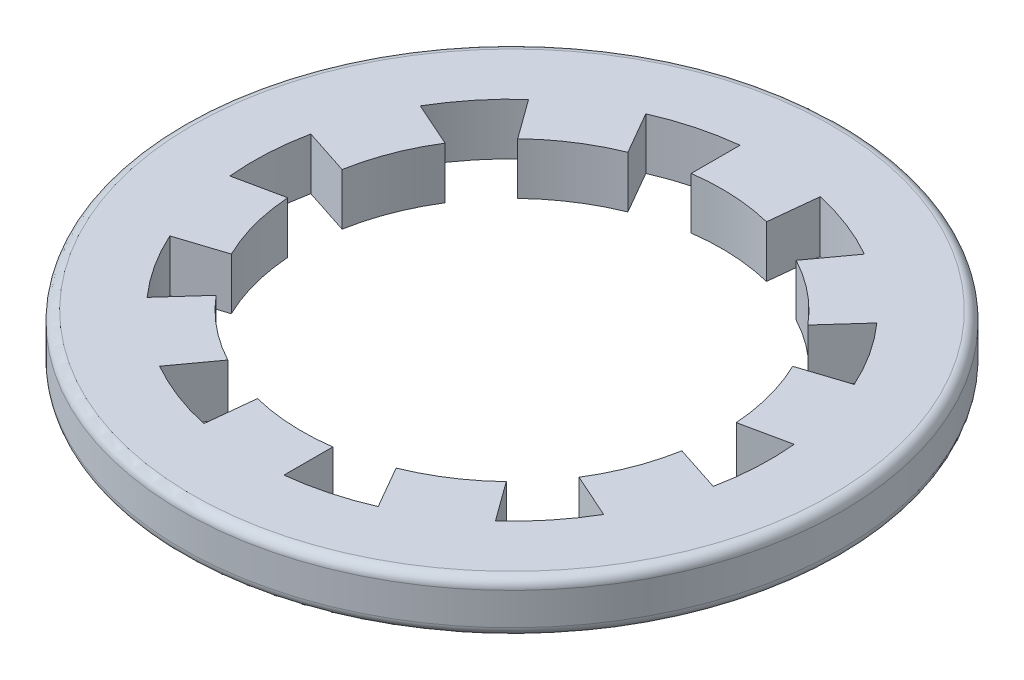
SolidWorks part; units mm, degrees
ref_plane "前视基准面" through (0, 0, 0) normal (0, 0, 1) x (1, 0, 0)
ref_plane "上视基准面" through (0, 0, 0) normal (0, 1, 0) x (1, 0, 0)
ref_plane "右视基准面" through (0, 0, 0) normal (1, 0, 0) x (0, 0, -1)
sketch "草图1" plane through (0, 0, 0) normal (0, 0, 1) x (1, 0, 0)
  line L0 (5.1, 69.1085) -> (0, 69.1085)
  line L1 (0, 69.1085) -> (0, 68.3085)
  line L2 (0, 68.3085) -> (5.1, 68.3085)
  line L3 (5.1, 68.3085) -> (5.1, 69.1085)
  line L4 (0, 69.1085) -> (0, 68.3085) construction
  dimension "D1" = 0.8
  dimension "D2" = 5.1
revolve "旋转1" add sketch "草图1" angle 360 about L4
sketch "草图2" plane through (0, 69.1085, 0) normal (0, 1, 0) x (-1, 0, 0)
  line L0 (-3.1996, 0.5704) -> (-3.9183, 0.8044)
  line L1 (-3.9814, -0.3852) -> (-3.242, -0.2285)
  line L2 (-2.9238, -1.4192) -> (-3.6428, -1.6523)
  line L3 (-2.9946, -2.6518) -> (-2.4885, -2.0904)
  line L4 (-1.5312, -2.8667) -> (-1.9759, -3.4779)
  line L5 (-0.864, -3.9056) -> (-0.7845, -3.1539)
  line L6 (0.4463, -3.2192) -> (0.4458, -3.9751)
  line L7 (1.5966, -3.6675) -> (1.2191, -3.0127)
  line L8 (2.2532, -2.3421) -> (2.6971, -2.9539)
  line L9 (3.4474, -2.0286) -> (2.7571, -1.7207)
  line L10 (3.1996, -0.5704) -> (3.9183, -0.8044)
  line L11 (3.9814, 0.3852) -> (3.242, 0.2285)
  line L12 (2.9238, 1.4192) -> (3.6428, 1.6523)
  line L13 (2.9946, 2.6518) -> (2.4885, 2.0904)
  line L14 (1.5312, 2.8667) -> (1.9759, 3.4779)
  line L15 (0.864, 3.9056) -> (0.7845, 3.1539)
  line L16 (-0.4463, 3.2192) -> (-0.4458, 3.9751)
  line L17 (-1.5966, 3.6675) -> (-1.2191, 3.0127)
  line L18 (-2.2532, 2.3421) -> (-2.6971, 2.9539)
  line L19 (-3.4474, 2.0286) -> (-2.7571, 1.7207)
  arc A0 (-2.7571, 1.7207) -> (-3.1996, 0.5704) centre (0, 0) ccw
  arc A1 (-3.9183, 0.8044) -> (-3.9814, -0.3852) centre (0, 0) ccw
  arc A2 (-3.242, -0.2285) -> (-2.9238, -1.4192) centre (0, 0) ccw
  arc A3 (-3.6428, -1.6523) -> (-2.9946, -2.6518) centre (0, 0) ccw
  arc A4 (-2.4885, -2.0904) -> (-1.5312, -2.8667) centre (0, 0) ccw
  arc A5 (-1.9759, -3.4779) -> (-0.864, -3.9056) centre (0, 0) ccw
  arc A6 (-0.7845, -3.1539) -> (0.4463, -3.2192) centre (0, 0) ccw
  arc A7 (0.4458, -3.9751) -> (1.5966, -3.6675) centre (0, 0) ccw
  arc A8 (1.2191, -3.0127) -> (2.2532, -2.3421) centre (0, 0) ccw
  arc A9 (2.6971, -2.9539) -> (3.4474, -2.0286) centre (0, 0) ccw
  arc A10 (2.7571, -1.7207) -> (3.1996, -0.5704) centre (0, 0) ccw
  arc A11 (3.9183, -0.8044) -> (3.9814, 0.3852) centre (0, 0) ccw
  arc A12 (3.242, 0.2285) -> (2.9238, 1.4192) centre (0, 0) ccw
  arc A13 (3.6428, 1.6523) -> (2.9946, 2.6518) centre (0, 0) ccw
  arc A14 (2.4885, 2.0904) -> (1.5312, 2.8667) centre (0, 0) ccw
  arc A15 (1.9759, 3.4779) -> (0.864, 3.9056) centre (0, 0) ccw
  arc A16 (0.7845, 3.1539) -> (-0.4463, 3.2192) centre (0, 0) ccw
  arc A17 (-0.4458, 3.9751) -> (-1.5966, 3.6675) centre (0, 0) ccw
  arc A18 (-1.2191, 3.0127) -> (-2.2532, 2.3421) centre (0, 0) ccw
  arc A19 (-2.6971, 2.9539) -> (-3.4474, 2.0286) centre (0, 0) ccw
extrude "切除-拉伸1" cut sketch "草图2" against normal through all
fillet "圆角1" radius 0.15 2 edges at (5.1, 69.1085, 0) (5.1, 68.3085, 0)
